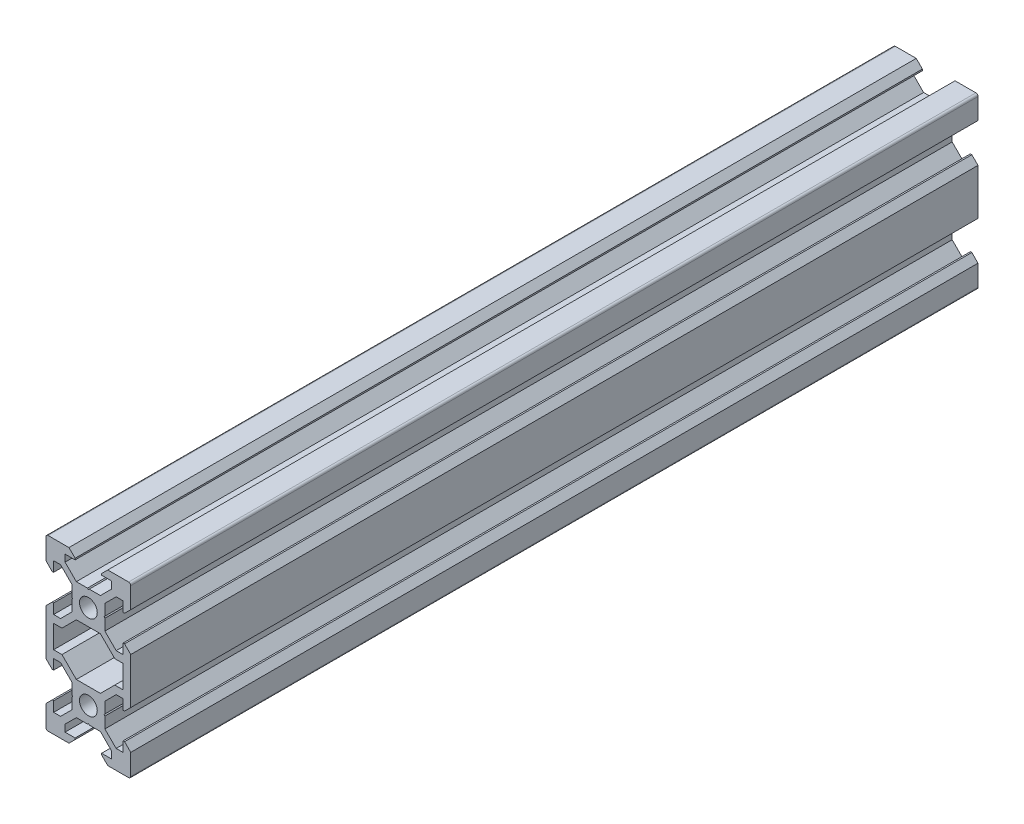
SolidWorks part; units mm, degrees
material "6061-T6 (SS)"
ref_plane "Front Plane" through (0, 0, 0) normal (0, 0, 1) x (1, 0, 0)
ref_plane "Top Plane" through (0, 0, 0) normal (0, 1, 0) x (1, 0, 0)
ref_plane "Right Plane" through (0, 0, 0) normal (1, 0, 0) x (0, 0, -1)
sketch "Sketch1" plane through (0, 0, 0) normal (0, 0, 1) x (1, 0, 0)
  line L0 (0, 0) -> (10, 0) construction
  line L1 (9.5, -20) -> (-9.5, -20)
  line L2 (10, -19.5) -> (10, 19.5)
  line L3 (9.5, 20) -> (-9.5, 20)
  line L4 (-10, -19.5) -> (-10, 19.5)
  line L5 (10, -20) -> (-10, 20) construction
  line L6 (10, 20) -> (-10, -20) construction
  circle A0 centre (0, 10) radius 2.1
  circle A1 centre (0, -10) radius 2.1
  arc A2 (-9.5, -20) -> (-10, -19.5) centre (-9.5, -19.5) cw
  arc A3 (9.5, -20) -> (10, -19.5) centre (9.5, -19.5) ccw
  arc A4 (10, 19.5) -> (9.5, 20) centre (9.5, 19.5) ccw
  arc A5 (-9.5, 20) -> (-10, 19.5) centre (-9.5, 19.5) ccw
  point P0 (0, 0)
  line B0 (0, 10) -> (0, 20) construction
  line B1 (0, 13.69) -> (-0.21, 13.9)
  line B2 (-0.21, 13.9) -> (-2.8393, 13.9)
  line B3 (-2.8393, 13.9) -> (-5.5, 16.5607)
  line B4 (-5.5, 16.5607) -> (-5.5, 18.2)
  line B5 (-5.5, 18.2) -> (-3.125, 18.2)
  line B6 (-3.125, 18.2) -> (-3.125, 18.545)
  line B7 (-3.125, 18.545) -> (-4.58, 20)
  line B8 (-4.58, 20) -> (4.58, 20)
  line B9 (0, 10) -> (-5.9132, 15.9132) construction
  line B10 (3.125, 18.545) -> (4.58, 20)
  line B11 (3.125, 18.2) -> (3.125, 18.545)
  line B12 (5.5, 18.2) -> (3.125, 18.2)
  line B13 (5.5, 16.5607) -> (5.5, 18.2)
  line B14 (2.8393, 13.9) -> (5.5, 16.5607)
  line B15 (0.21, 13.9) -> (2.8393, 13.9)
  line B16 (0, 13.69) -> (0.21, 13.9)
  line B17 (0, 10) -> (-10, 10) construction
  line B18 (-3.69, 10) -> (-3.9, 9.79)
  line B19 (-3.9, 9.79) -> (-3.9, 7.1607)
  line B20 (-3.9, 7.1607) -> (-6.5607, 4.5)
  line B21 (-6.5607, 4.5) -> (-8.2, 4.5)
  line B22 (-8.2, 4.5) -> (-8.2, 6.875)
  line B23 (-8.2, 6.875) -> (-8.545, 6.875)
  line B24 (-8.545, 6.875) -> (-10, 5.42)
  line B25 (-10, 5.42) -> (-10, 14.58)
  line B26 (0, 10) -> (-5.9132, 4.0868) construction
  line B27 (-8.545, 13.125) -> (-10, 14.58)
  line B28 (-8.2, 13.125) -> (-8.545, 13.125)
  line B29 (-8.2, 15.5) -> (-8.2, 13.125)
  line B30 (-6.5607, 15.5) -> (-8.2, 15.5)
  line B31 (-3.9, 12.8393) -> (-6.5607, 15.5)
  line B32 (-3.9, 10.21) -> (-3.9, 12.8393)
  line B33 (-3.69, 10) -> (-3.9, 10.21)
  line B34 (0, -10) -> (-10, -10) construction
  line B35 (-3.69, -10) -> (-3.9, -10.21)
  line B36 (-3.9, -10.21) -> (-3.9, -12.8393)
  line B37 (-3.9, -12.8393) -> (-6.5607, -15.5)
  line B38 (-6.5607, -15.5) -> (-8.2, -15.5)
  line B39 (-8.2, -15.5) -> (-8.2, -13.125)
  line B40 (-8.2, -13.125) -> (-8.545, -13.125)
  line B41 (-8.545, -13.125) -> (-10, -14.58)
  line B42 (-10, -14.58) -> (-10, -5.42)
  line B43 (0, -10) -> (-5.9132, -15.9132) construction
  line B44 (-8.545, -6.875) -> (-10, -5.42)
  line B45 (-8.2, -6.875) -> (-8.545, -6.875)
  line B46 (-8.2, -4.5) -> (-8.2, -6.875)
  line B47 (-6.5607, -4.5) -> (-8.2, -4.5)
  line B48 (-3.9, -7.1607) -> (-6.5607, -4.5)
  line B49 (-3.9, -9.79) -> (-3.9, -7.1607)
  line B50 (-3.69, -10) -> (-3.9, -9.79)
  line B51 (0, -10) -> (0, -20) construction
  line B52 (0, -13.69) -> (0.21, -13.9)
  line B53 (0.21, -13.9) -> (2.8393, -13.9)
  line B54 (2.8393, -13.9) -> (5.5, -16.5607)
  line B55 (5.5, -16.5607) -> (5.5, -18.2)
  line B56 (5.5, -18.2) -> (3.125, -18.2)
  line B57 (3.125, -18.2) -> (3.125, -18.545)
  line B58 (3.125, -18.545) -> (4.58, -20)
  line B59 (4.58, -20) -> (-4.58, -20)
  line B60 (0, -10) -> (5.9132, -15.9132) construction
  line B61 (-3.125, -18.545) -> (-4.58, -20)
  line B62 (-3.125, -18.2) -> (-3.125, -18.545)
  line B63 (-5.5, -18.2) -> (-3.125, -18.2)
  line B64 (-5.5, -16.5607) -> (-5.5, -18.2)
  line B65 (-2.8393, -13.9) -> (-5.5, -16.5607)
  line B66 (-0.21, -13.9) -> (-2.8393, -13.9)
  line B67 (0, -13.69) -> (-0.21, -13.9)
  line B68 (0, -10) -> (10, -10) construction
  line B69 (3.69, -10) -> (3.9, -9.79)
  line B70 (3.9, -9.79) -> (3.9, -7.1607)
  line B71 (3.9, -7.1607) -> (6.5607, -4.5)
  line B72 (6.5607, -4.5) -> (8.2, -4.5)
  line B73 (8.2, -4.5) -> (8.2, -6.875)
  line B74 (8.2, -6.875) -> (8.545, -6.875)
  line B75 (8.545, -6.875) -> (10, -5.42)
  line B76 (10, -5.42) -> (10, -14.58)
  line B77 (0, -10) -> (5.9132, -4.0868) construction
  line B78 (8.545, -13.125) -> (10, -14.58)
  line B79 (8.2, -13.125) -> (8.545, -13.125)
  line B80 (8.2, -15.5) -> (8.2, -13.125)
  line B81 (6.5607, -15.5) -> (8.2, -15.5)
  line B82 (3.9, -12.8393) -> (6.5607, -15.5)
  line B83 (3.9, -10.21) -> (3.9, -12.8393)
  line B84 (3.69, -10) -> (3.9, -10.21)
  line B85 (0, 10) -> (10, 10) construction
  line B86 (3.69, 10) -> (3.9, 10.21)
  line B87 (3.9, 10.21) -> (3.9, 12.8393)
  line B88 (3.9, 12.8393) -> (6.5607, 15.5)
  line B89 (6.5607, 15.5) -> (8.2, 15.5)
  line B90 (8.2, 15.5) -> (8.2, 13.125)
  line B91 (8.2, 13.125) -> (8.545, 13.125)
  line B92 (8.545, 13.125) -> (10, 14.58)
  line B93 (10, 14.58) -> (10, 5.42)
  line B94 (0, 10) -> (5.9132, 15.9132) construction
  line B95 (8.545, 6.875) -> (10, 5.42)
  line B96 (8.2, 6.875) -> (8.545, 6.875)
  line B97 (8.2, 4.5) -> (8.2, 6.875)
  line B98 (6.5607, 4.5) -> (8.2, 4.5)
  line B99 (3.9, 7.1607) -> (6.5607, 4.5)
  line B100 (3.9, 9.79) -> (3.9, 7.1607)
  line B101 (3.69, 10) -> (3.9, 9.79)
  line B102 (-8.2, -2.7) -> (-8.2, 2.7)
  line B103 (-8.2, 2.7) -> (-6.2393, 2.7)
  line B104 (-6.2393, 2.7) -> (-2.8393, 6.1)
  line B105 (-2.8393, 6.1) -> (2.8393, 6.1)
  line B106 (0, 6.1) -> (0, 0) construction
  line B107 (0, 0) -> (-8.2, 0) construction
  line B108 (6.2393, 2.7) -> (2.8393, 6.1)
  line B109 (8.2, 2.7) -> (6.2393, 2.7)
  line B110 (8.2, -2.7) -> (8.2, 2.7)
  line B111 (8.2, -2.7) -> (6.2393, -2.7)
  line B112 (6.2393, -2.7) -> (2.8393, -6.1)
  line B113 (-2.8393, -6.1) -> (2.8393, -6.1)
  line B114 (-6.2393, -2.7) -> (-2.8393, -6.1)
  line B115 (-8.2, -2.7) -> (-6.2393, -2.7)
  line B116 (0, 6.1) -> (0, 10) construction
  line B117 (0, 10) -> (-5.0927, 4.9073) construction
  dimension "D4" = 4.2
  dimension "D5" = 0.5
  dimension "D1" = 20
  dimension "D2" = 40
  dimension "D3" = 20
sketch_block_instance "V Slot 1-4"
sketch_block "V Slot 1" parameters "D1"=10, "D2"=11, "D3"=4.3, "D4"=1.8, "D5"=0.21, "D6"=45, "D7"=9.16, "D8"=1.5, "D9"=6.25
sketch_block_instance "V Slot 1-5"
sketch_block_instance "V Slot 1-6"
sketch_block_instance "V Slot 1-7"
sketch_block_instance "V Slot 1-8"
sketch_block_instance "V Slot 1-9"
sketch_block_instance "Center Cutout 1-1"
sketch_block "Center Cutout 1" parameters "D1"=5.4, "D2"=12.2, "D3"=8.2, "D4"=45, "D5"=10, "D6"=1.5
extrude "Boss-Extrude1" add sketch "Sketch1" along normal blind 200 contours B101 B86 B87 B88 B89 B90 B91 B92 L2 A4 L3 B10 B11 B12 B13 B14 B15 B16 B1 B2 B3 B4 B5 B6 B7 A5 L4 B27 B28 B29 B30 B31 B32 B33 B18 B19 B20 B21 B22 B23 B24 B44 B45 B46 B47 B48 B49 B50 B35
equation "\"L\"= 200"
equation "\"D1@Boss-Extrude1\"=\"L\""
